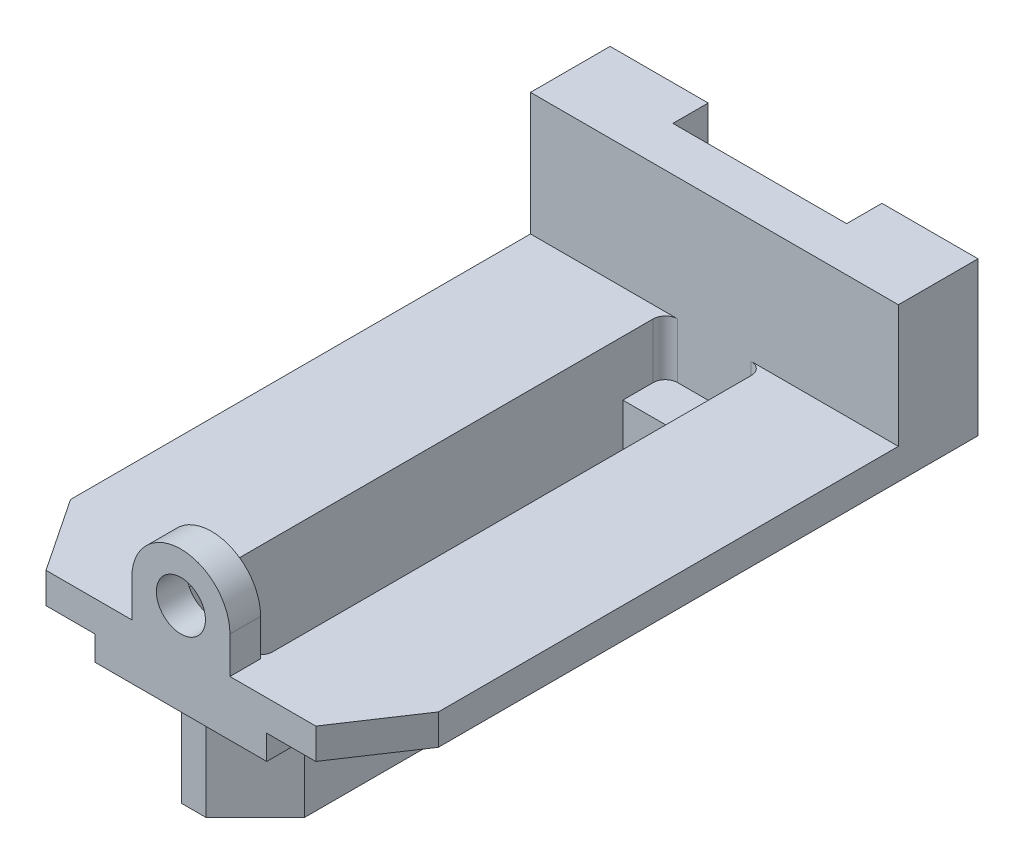
SolidWorks part; units mm, degrees
material "Cast Alloy Steel"
ref_plane "Front Plane" through (0, 0, 0) normal (0, 0, 1) x (1, 0, 0)
ref_plane "Top Plane" through (0, 0, 0) normal (0, 1, 0) x (1, 0, 0)
ref_plane "Right Plane" through (0, 0, 0) normal (1, 0, 0) x (0, 0, -1)
sketch "Sketch1" plane through (0, 0, 0) normal (0, 0, 1) x (1, 0, 0)
  line L0 (28, 4) -> (44, 4)
  line L1 (0, 0) -> (28, 0)
  line L2 (0, 0) -> (0, 4)
  line L4 (28, 0) -> (28, 4)
  line L5 (-16, 4) -> (0, 4)
  line L6 (-16, 4) -> (-16, 9)
  line L7 (-16, 9) -> (44, 9)
  line L8 (44, 4) -> (44, 9)
  point P11 (0, 0)
  point P12 (0, 0)
  point P13 (0, 0)
  point P14 (0, 0)
  dimension "D1" = 28
  dimension "D2" = 4
  dimension "D3" = 60
  dimension "D4" = 16
  dimension "D5" = 5
extrude "Boss-Extrude1" add sketch "Sketch1" along normal blind 100
sketch "Sketch2" plane through (0, 0, 100) normal (0, 0, 1) x (1, 0, 0)
  line L0 (14, 0) -> (14, 17.2037) construction
  line L1 (0, 0) -> (28, 0) construction
  line L4 (6, 15) -> (6, 0)
  line L5 (6, 0) -> (22, 0)
  line L6 (22, 15) -> (22, 0)
  circle A0 centre (14, 15) radius 4
  arc A1 (22, 15) -> (6, 15) centre (14, 15) ccw
  dimension "D1" = 8
  dimension "D3" = 16
  dimension "D2" = 15
extrude "Boss-Extrude2" add sketch "Sketch2" against normal blind 5 contours A1 L4 L5 L6
sketch "Sketch3" plane through (0, 9, 0) normal (0, 1, 0) x (1, 0, 0)
  line L0 (36, -100) -> (44, -88)
  line L1 (22, -100) -> (44, -100) construction
  line L2 (44, -100) -> (44, 0) construction
  line L3 (44, -88) -> (44, -100)
  line L4 (44, -100) -> (36, -100)
  line L5 (-8, -100) -> (-16, -100)
  line L6 (-16, -100) -> (6, -100) construction
  line L7 (-16, -100) -> (-16, -88)
  line L8 (-16, -100) -> (-16, 0) construction
  line L9 (-16, -88) -> (-8, -100)
  dimension "D1" = 12
  dimension "D2" = 12
  dimension "D3" = 8
  dimension "D4" = 8
extrude "Cut-Extrude1" cut sketch "Sketch3" against normal through all contours L0 L3 L4
sketch "Sketch5" plane through (0, 9, 0) normal (0, 1, 0) x (1, 0, 0)
  line L0 (-16, -88) -> (-16, 0) construction
  line L1 (-16, 0) -> (0, 0)
  line L2 (-16, 0) -> (-16, -12.9862)
  line L3 (-16, -12.9862) -> (44, -12.9862)
  line L4 (44, 0) -> (44, -12.9862)
  line L5 (44, -88) -> (44, 0) construction
  line L6 (28.3291, 0) -> (44, 0)
  line L8 (0, 0) -> (0, -5.7564)
  line L9 (0, -5.7564) -> (28.3291, -5.7564)
  line L10 (28.3291, 0) -> (28.3291, -5.7564)
extrude "Boss-Extrude3" add sketch "Sketch5" along normal blind 20
sketch "Sketch6" plane through (0, 9, 0) normal (0, 1, 0) x (1, 0, 0)
  line L0 (-16, -12.9862) -> (44, -12.9862) construction
  line L1 (6, -12.9862) -> (22, -12.9862)
  line L2 (6, -12.9862) -> (6, -95)
  line L3 (6, -95) -> (22, -95)
  line L4 (22, -12.9862) -> (22, -95)
  line L5 (6, -95) -> (6, -100) construction
extrude "Cut-Extrude2" cut sketch "Sketch6" against normal blind 20 contours L4 L3 L2 L1
fillet "Fillet1" radius 2 4 edges at (22, 4.5, 12.9862) (6, 4.5, 12.9862) (22, 4.5, 95) (6, 4.5, 95)
sketch "Sketch7" plane through (0, 0, 0) normal (0, -1, 0) x (1, 0, 0)
  line L0 (28, 100) -> (28, 0) construction
  line L1 (4, 97.8693) -> (24, 97.8693)
  line L2 (4, 97.8693) -> (4, 7.8264)
  line L3 (4, 7.8264) -> (24, 7.8264)
  line L4 (24, 97.8693) -> (24, 7.8264)
  line L5 (6, 14.9862) -> (6, 93) construction
  line L6 (6, 86.614) -> (22, 86.614)
  line L7 (6, 86.614) -> (6, 19.9218)
  line L8 (6, 19.9218) -> (22, 19.9218)
  line L9 (22, 86.614) -> (22, 19.9218)
  line L10 (22, 14.9862) -> (22, 93) construction
  dimension "D1" = 20
  dimension "D2" = 4
extrude "Boss-Extrude4" add sketch "Sketch7" along normal blind 15 contours L4 L3 L2 L1
chamfer "Chamfer1" distance 8 angle 45 4 edges at (24, -7.5, 7.8264) (4, -7.5, 7.8264) (4, -7.5, 97.8693) (24, -7.5, 97.8693)
